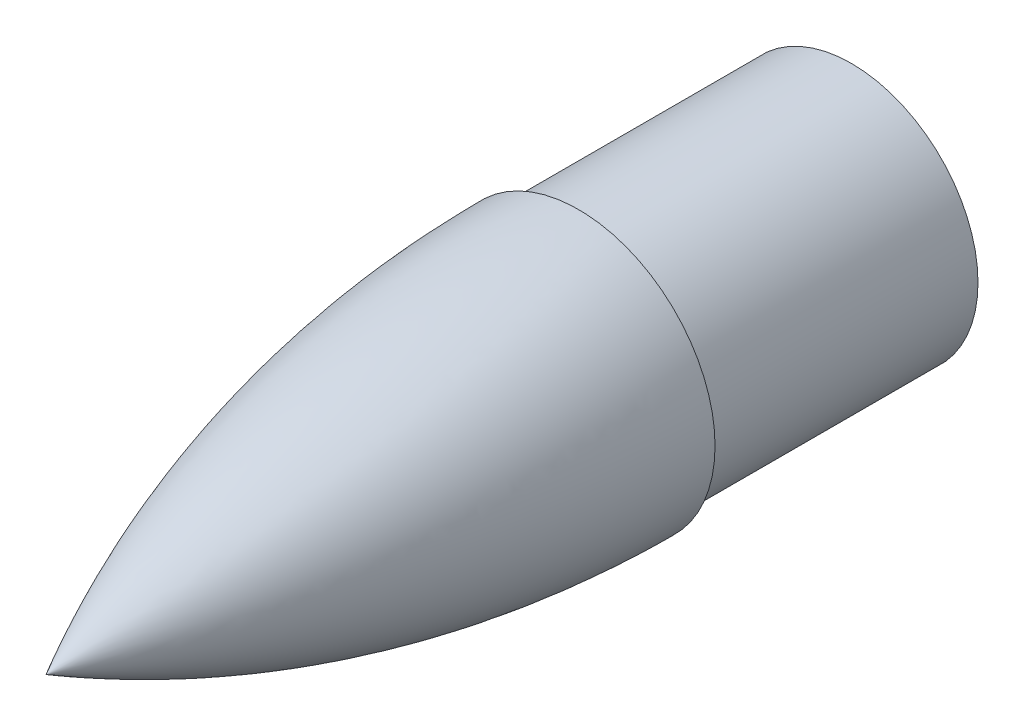
SolidWorks part; units mm, degrees
ref_plane "Alzado" through (0, 0, 0) normal (0, 0, 1) x (1, 0, 0)
ref_plane "Planta" through (0, 0, 0) normal (0, 1, 0) x (1, 0, 0)
ref_plane "Vista lateral" through (0, 0, 0) normal (1, 0, 0) x (0, 0, -1)
sketch "Croquis1" plane through (0, 0, 0) normal (1, 0, 0) x (0, 0, -1)
  line L0 (0, 291.6951) -> (0, 332.6951) construction
  line L1 (-160, 291.6951) -> (0, 291.6951) construction
  line L2 (0, 332.6951) -> (0, 329.6951)
  line L3 (0, 329.6951) -> (82, 329.6951)
  line L4 (82, 329.6951) -> (82, 291.6951)
  line L5 (-4.522, 328.1419) -> (-4.522, 325.1731)
  line L6 (-4.522, 325.1731) -> (77.478, 325.1731)
  line L7 (77.478, 325.1731) -> (77.478, 291.6951)
  line L8 (77.478, 325.1731) -> (77.478, 291.6951) construction
  line L9 (-160, 291.6951) -> (-150.3713, 291.6951)
  line L10 (77.478, 291.6951) -> (82, 291.6951)
  line L11 (-160, 291.6951) -> (82, 291.6951) construction
  line L12 (-160, 291.6951) -> (-224.4578, 291.6951) construction
  arc A0 (0, 332.6951) -> (-160, 291.6951) centre (0, 0) ccw
  arc A1 (-4.522, 328.1419) -> (-150.3713, 291.6951) centre (0, 0) ccw
  arc A2 (-4.522, 328.1419) -> (-157.8253, 287.7304) centre (0, 0) ccw construction
  point P14 (0, 0)
  dimension "D1" = 160
  dimension "D2" = 82
  dimension "D3" = 38
  dimension "D4" = 3
revolve "Revolución2" add sketch "Croquis1" angle 360 about L12
